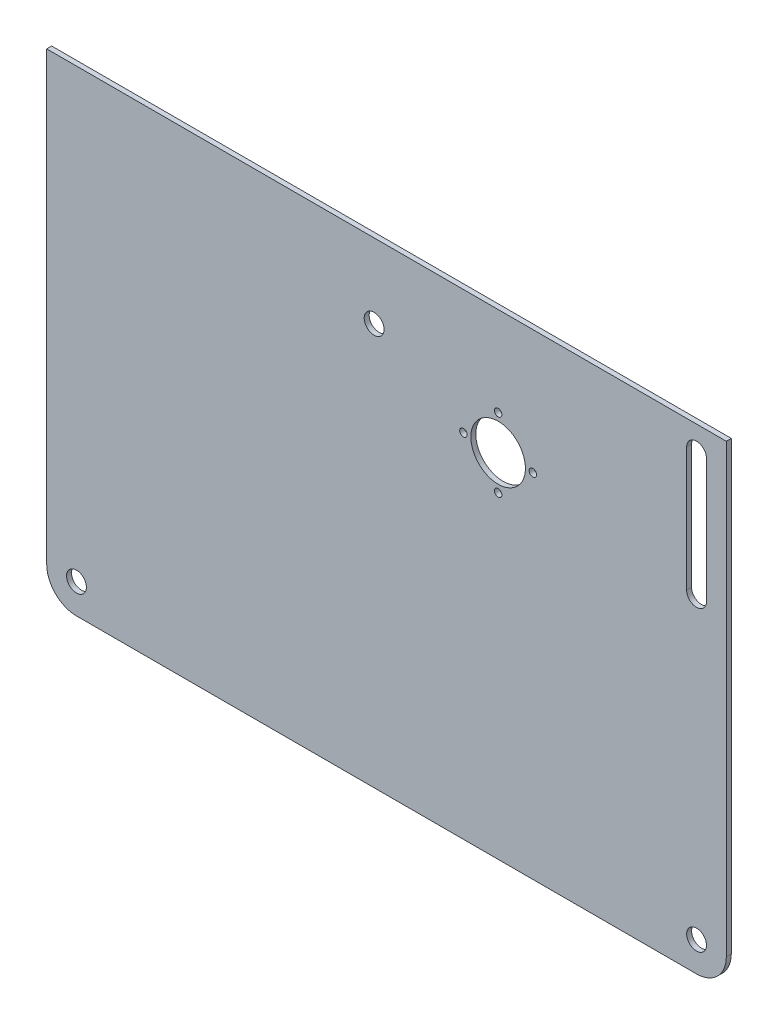
SolidWorks part; units mm, degrees
ref_plane "Front Plane" through (0, 0, 0) normal (0, 0, 1) x (1, 0, 0)
ref_plane "Top Plane" through (0, 0, 0) normal (0, 1, 0) x (1, 0, 0)
ref_plane "Right Plane" through (0, 0, 0) normal (1, 0, 0) x (0, 0, -1)
sketch "Sketch1" plane through (0, 0, 0) normal (0, 0, 1) x (1, 0, 0)
  line L0 (1.1, 0) -> (-1.1, 0) construction
  line L1 (0, 53.2731) -> (0, -38.9774) construction
  line L2 (0, -1.1) -> (0, 1.1) construction
  line L3 (-125, -12) -> (125, -12)
  line L4 (121, 120) -> (129, 120)
  line L5 (121, 120) -> (121, 170)
  line L6 (121, 170) -> (129, 170)
  line L7 (129, 120) -> (129, 170)
  line L8 (121, 120) -> (129, 170) construction
  line L9 (121, 170) -> (129, 120) construction
  line L10 (158.4448, 180) -> (-53.9982, 180)
  line L11 (137, 0) -> (137, 180)
  line L12 (137, 180) -> (158.4448, 180)
  line L13 (-53.9982, 180) -> (-137, 180)
  line L14 (-137, 180) -> (-137, 0)
  circle A0 centre (-125, 0) radius 4
  circle A1 centre (125, 0) radius 4
  circle A2 centre (125, 170) radius 4
  circle A3 centre (45, 130) radius 11
  circle A4 centre (-5, 150) radius 4
  circle A5 centre (125, 120) radius 4
  arc A6 (-125, -12) -> (-137, 0) centre (-125, 0) cw
  arc A7 (125, -12) -> (137, 0) centre (125, 0) ccw
  circle A8 centre (45, 130) radius 14 construction
  circle A9 centre (45, 144) radius 1.5
  circle A10 centre (59, 130) radius 1.5
  circle A11 centre (45, 116) radius 1.5
  circle A12 centre (31, 130) radius 1.5
  point P17 (125, 145)
  point P35 (89, 130)
  point P44 (45, 130)
  dimension "D2" = 8
  dimension "D4" = 22
  dimension "D11" = 12
  dimension "D13" = 12
  dimension "D14" = 28
  dimension "D15" = 3
  dimension "D1" = 250
  dimension "D3" = 250
  dimension "D5" = 120
  dimension "D6" = 150
  dimension "D7" = 130
  dimension "D8" = 170
  dimension "D9" = 145
  dimension "D10" = 50
  dimension "D12" = 10
  dimension "D16" = 4
extrude "Boss-Extrude1" add sketch "Sketch1" along normal blind 2 contours L3 A7 L11 L12 L10 L13 L14 A6 A0 A1 A3 A4 A5 L5 A2 L7
